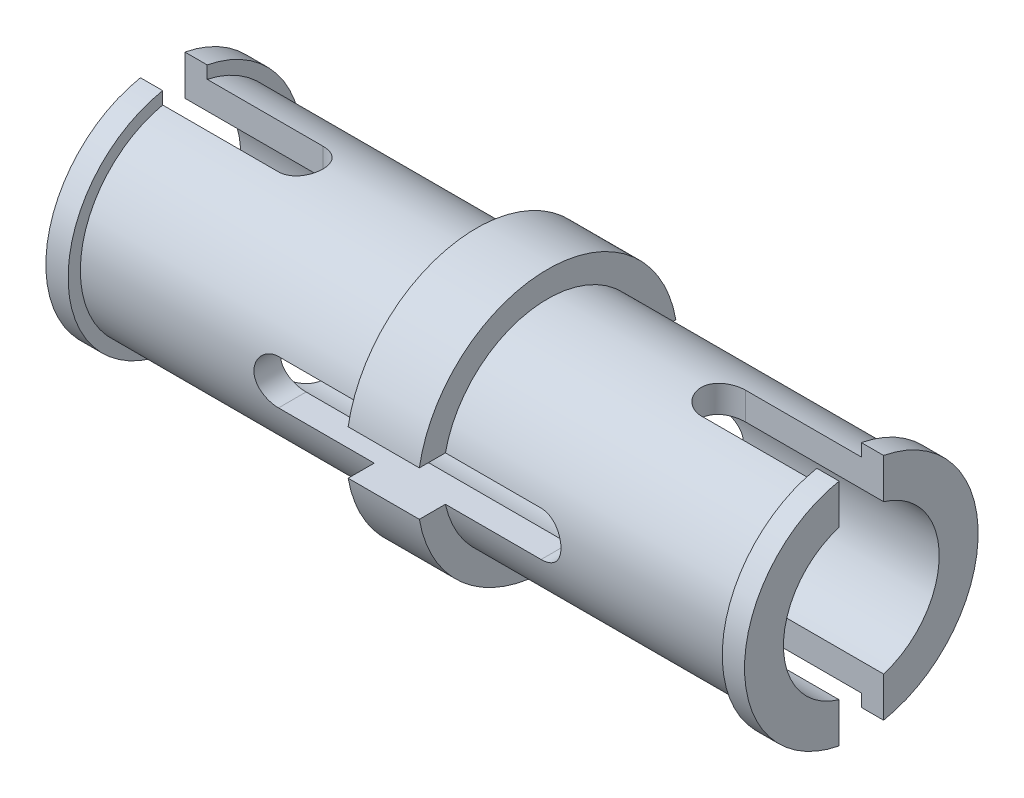
SolidWorks part; units mm, degrees
ref_plane "Front Plane" through (0, 0, 0) normal (0, 0, 1) x (1, 0, 0)
ref_plane "Top Plane" through (0, 0, 0) normal (0, 1, 0) x (1, 0, 0)
ref_plane "Right Plane" through (0, 0, 0) normal (1, 0, 0) x (0, 0, -1)
sketch "Sketch1" plane through (0, 0, 0) normal (1, 0, 0) x (0, 0, -1)
  circle A0 centre (0, 0) radius 1.75
  circle A1 centre (0, 0) radius 2.925
  dimension "D1" = 3.5
  dimension "D2" = 5.85
extrude "Middle Ring" add sketch "Sketch1" along normal mid plane 1.6
sketch "Sketch2" plane through (0, 0, 0) normal (1, 0, 0) x (0, 0, -1)
  circle A0 centre (0, 0) radius 1.75 construction
  circle A1 centre (0, 0) radius 1.75
  circle A2 centre (0, 0) radius 2.35
  dimension "D1" = 4.7
extrude "Outer Body" add sketch "Sketch2" along normal mid plane 14.7
sketch "Sketch3" plane through (7.35, 0, 0) normal (1, 0, 0) x (0, 0, -1)
  circle A0 centre (0, 0) radius 1.75 construction
  circle A1 centre (0, 0) radius 1.75
  circle A2 centre (0, 0) radius 2.625
  dimension "D1" = 5.25
extrude "Outer Rim" add sketch "Sketch3" along normal blind 0.5
mirror "Mirror1" about plane through (0, 0, 0) normal (1, 0, 0) of "Outer Rim"
sketch "Sketch4" plane through (0, 0, 0) normal (0, 0, 1) x (1, 0, 0)
  line L0 (2.95, 0) -> (-2.95, 0) construction
  line L1 (2.95, -0.5) -> (-2.95, -0.5)
  line L2 (2.95, 0.5) -> (-2.95, 0.5)
  arc A0 (2.95, -0.5) -> (2.95, 0.5) centre (2.95, 0) ccw
  arc A1 (-2.95, 0.5) -> (-2.95, -0.5) centre (-2.95, 0) ccw
  point P2 (0, 0)
  dimension "D2" = 6.9
  dimension "D1" = 1
extrude "Middle Slot " cut sketch "Sketch4" against normal through all both and the other way through all
sketch "Sketch5" plane through (0, 0, 0) normal (0, 1, 0) x (1, 0, 0)
  line L0 (10.95, 0) -> (4.75, 0) construction
  line L1 (7.85, -2.625) -> (7.85, 2.625) construction
  line L2 (10.95, -0.5) -> (4.75, -0.5)
  line L3 (10.95, 0.5) -> (4.75, 0.5)
  line L4 (0, 0) -> (0, 3.8777) construction
  line L5 (-10.95, 0) -> (-4.75, 0) construction
  line L6 (-10.95, -0.5) -> (-4.75, -0.5)
  line L7 (-10.95, 0.5) -> (-4.75, 0.5)
  arc A0 (10.95, -0.5) -> (10.95, 0.5) centre (10.95, 0) ccw
  arc A1 (4.75, 0.5) -> (4.75, -0.5) centre (4.75, 0) ccw
  arc A2 (-10.95, -0.5) -> (-10.95, 0.5) centre (-10.95, 0) cw
  arc A3 (-4.75, 0.5) -> (-4.75, -0.5) centre (-4.75, 0) cw
  point P5 (7.85, 0)
  point P14 (-7.85, 0)
  dimension "D2" = 8.5
  dimension "D1" = 1
  dimension "D3" = 3.6
extrude "Side Slots" cut sketch "Sketch5" against normal through all both and the other way through all
